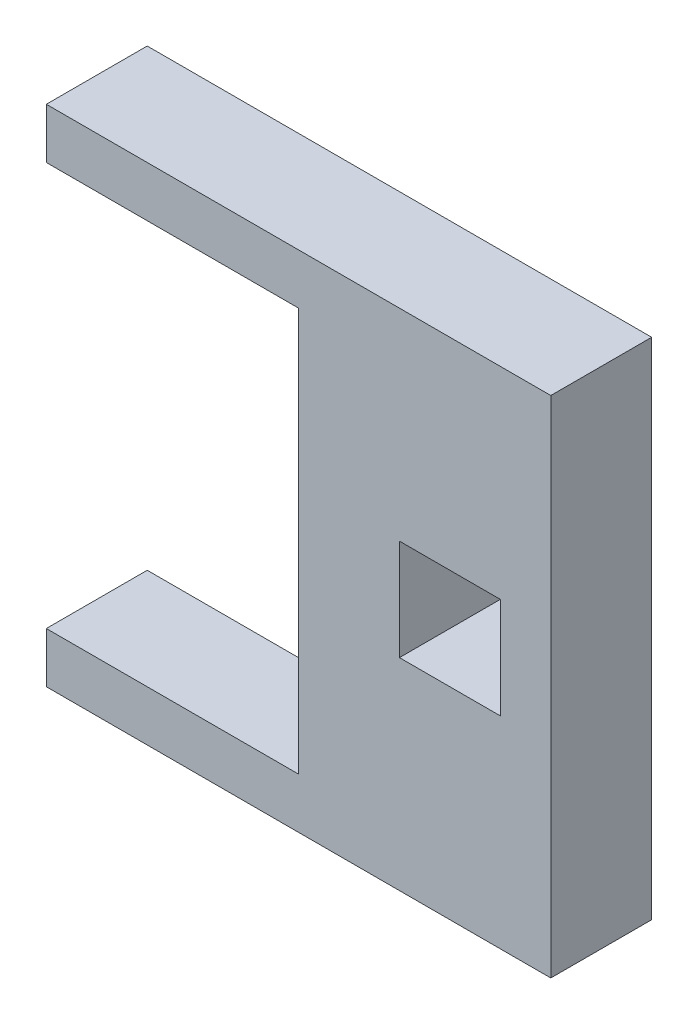
SolidWorks part; units mm, degrees
ref_plane "Front Plane" through (0, 0, 0) normal (0, 0, 1) x (1, 0, 0)
ref_plane "Top Plane" through (0, 0, 0) normal (0, 1, 0) x (1, 0, 0)
ref_plane "Right Plane" through (0, 0, 0) normal (1, 0, 0) x (0, 0, -1)
sketch "Sketch1" plane through (0, 0, 0) normal (0, 0, 1) x (1, 0, 0)
  line L0 (0, 45) -> (25, 45)
  line L1 (0, 0) -> (50, 0)
  line L2 (0, 0) -> (0, 5)
  line L3 (0, 50) -> (50, 50)
  line L4 (50, 0) -> (50, 50)
  line L5 (45, 30) -> (35, 30)
  line L6 (45, 30) -> (45, 20)
  line L7 (45, 20) -> (35, 20)
  line L8 (35, 30) -> (35, 20)
  line L9 (25, 45) -> (25, 5)
  line L10 (25, 5) -> (0, 5)
  line L11 (0, 45) -> (0, 50)
  dimension "D1" = 10
  dimension "D2" = 50
  dimension "D3" = 5
  dimension "D4" = 20
  dimension "D5" = 5
  dimension "D6" = 50
  dimension "D7" = 5
  dimension "D8" = 25
extrude "Boss-Extrude1" add sketch "Sketch1" along normal blind 10
